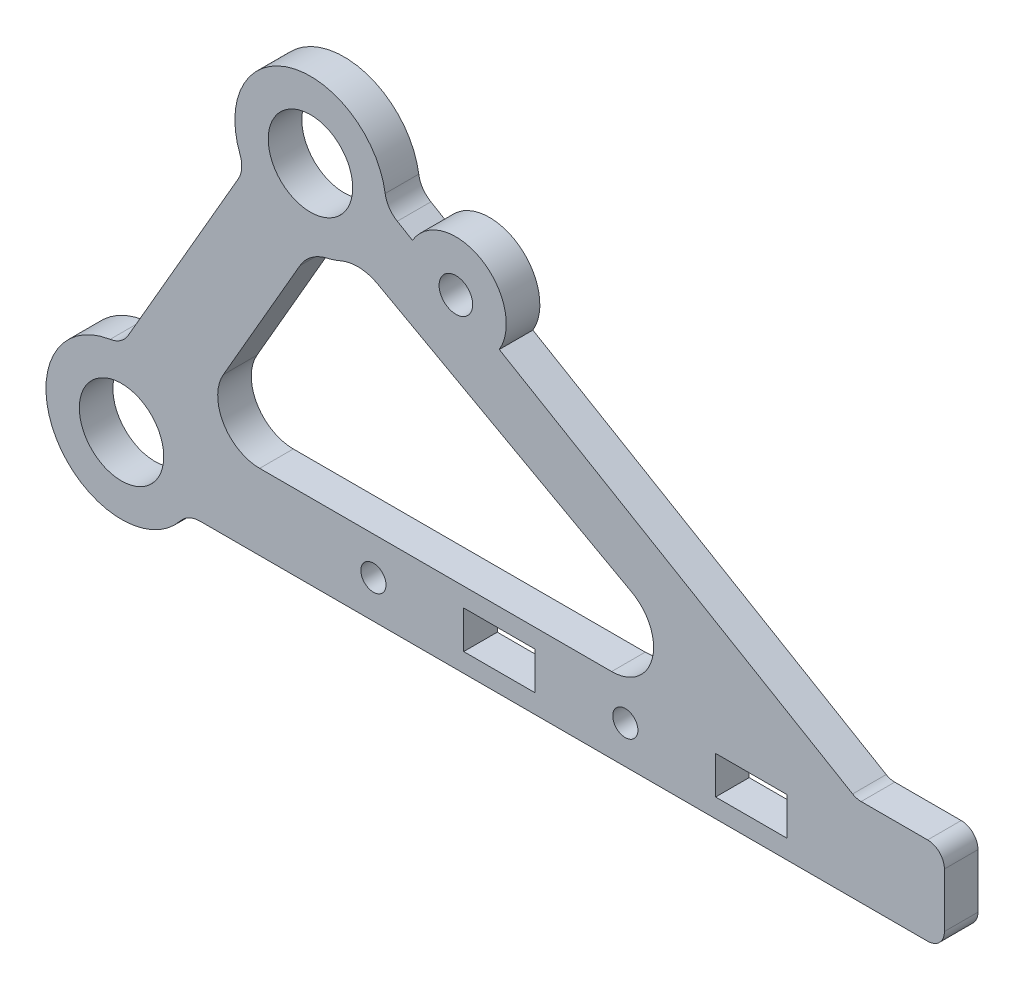
SolidWorks part; units mm, degrees
ref_plane "前视基准面" through (0, 0, 0) normal (0, 0, 1) x (1, 0, 0)
ref_plane "上视基准面" through (0, 0, 0) normal (0, 1, 0) x (1, 0, 0)
ref_plane "右视基准面" through (0, 0, 0) normal (1, 0, 0) x (0, 0, -1)
sketch "草图1" plane through (0, 0, 0) normal (0, 0, 1) x (1, 0, 0)
  line L0 (60, 0) -> (60, 0.846) construction
  line L1 (0, 0) -> (22.5, 38.9711) construction
  line L6 (0, 0) -> (30, 0) construction
  line L7 (60, 0) -> (45, 0) construction
  line L8 (87, -4.5) -> (9.3675, -4.5)
  line L9 (40.75, 2.25) -> (49.25, 2.25)
  line L10 (40.75, 2.25) -> (40.75, -2.25)
  line L11 (40.75, -2.25) -> (49.25, -2.25)
  line L12 (49.25, 2.25) -> (49.25, -2.25)
  line L13 (40.75, 2.25) -> (49.25, -2.25) construction
  line L14 (40.75, -2.25) -> (49.25, 2.25) construction
  line L16 (0.7866, 10.3625) -> (13.9191, 33.1087)
  line L17 (21.2554, 27.8154) -> (12.1244, 12)
  line L20 (30.5219, 30.5259) -> (60.7776, 13.8808)
  line L21 (32.8422, 38.1803) -> (87.0684, 6.2274)
  line L22 (16.4545, 4.5) -> (58.3675, 4.5)
  line L23 (60, 0) -> (98, 0) construction
  line L24 (98, 0) -> (98, -2.5)
  line L25 (96, -4.5) -> (87, -4.5)
  line L26 (88.0838, 5.9505) -> (96, 5.9505)
  line L27 (98, 3.9505) -> (98, 0)
  line L28 (70.75, 2.25) -> (70.75, -2.25)
  line L29 (79.25, -2.25) -> (70.75, -2.25)
  line L30 (79.25, 2.25) -> (79.25, -2.25)
  line L31 (79.25, 2.25) -> (70.75, 2.25)
  circle A0 centre (0, 0) radius 5.03
  circle A1 centre (22.5, 38.9711) radius 5.03
  circle A2 centre (0, 0) radius 9 construction
  circle A4 centre (22.5, 38.9711) radius 9 construction
  circle A6 centre (30, 0) radius 1.5
  arc A7 (-1.3586, 8.8969) -> (7.0256, -5.625) centre (0, 0) ccw
  arc A9 (14.1158, 35.6993) -> (31.3989, 40.3165) centre (22.5, 38.9711) cw
  arc A10 (24.4835, 30.1924) -> (26.1076, 30.7258) centre (22.5, 38.9711) ccw
  arc A11 (58.3675, 4.5) -> (60.7776, 13.8808) centre (58.3675, 9.5) ccw
  arc A12 (30.5219, 30.5259) -> (26.1076, 30.7258) centre (28.1118, 26.1451) ccw
  arc A13 (24.4835, 30.1924) -> (21.2554, 27.8154) centre (25.5855, 25.3154) ccw
  arc A14 (12.1244, 12) -> (16.4545, 4.5) centre (16.4545, 9.5) ccw
  arc A17 (9.3675, -4.5) -> (7.0256, -5.625) centre (9.3675, -7.5) ccw
  arc A18 (-1.3586, 8.8969) -> (0.7866, 10.3625) centre (-1.8114, 11.8625) ccw
  arc A19 (13.9191, 33.1087) -> (14.1158, 35.6993) centre (11.3211, 34.6087) ccw
  arc A20 (32.8422, 38.1803) -> (31.3989, 40.3165) centre (34.3652, 40.7649) cw
  circle A21 centre (60, 0) radius 1.5
  arc A22 (87.0684, 6.2274) -> (88.0838, 5.9505) centre (88.0838, 7.9505) ccw
  arc A23 (96, -4.5) -> (98, -2.5) centre (96, -2.5) ccw
  arc A24 (98, 3.9505) -> (96, 5.9505) centre (96, 3.9505) ccw
  point P35 (22.5, 29.9711)
  point P38 (7.7942, 4.5)
  point P45 (7.7942, -4.5)
  point P48 (0, 9)
  point P51 (14.7058, 34.4711)
  dimension "D1" = 2
  dimension "D2" = 5
  dimension "D3" = 15
  dimension "D5" = 3
  dimension "D6" = 15
extrude "凸台-拉伸1" add sketch "草图1" along normal blind 4
sketch "草图2" plane through (0, 0, 4) normal (0, 0, 1) x (1, 0, 0)
  line L1 (87.0684, 6.2274) -> (32.8422, 38.1803) construction
  line L2 (39.8196, 34.0688) -> (22.5, 38.9711) construction
  circle A0 centre (39.8196, 34.0688) radius 6
extrude "凸台-拉伸2" add sketch "草图2" against normal blind 4
sketch "草图3" plane through (0, 0, 4) normal (0, 0, 1) x (1, 0, 0)
  circle A0 centre (39.8196, 34.0688) radius 2
extrude "切除-拉伸1" cut sketch "草图3" against normal blind 4
